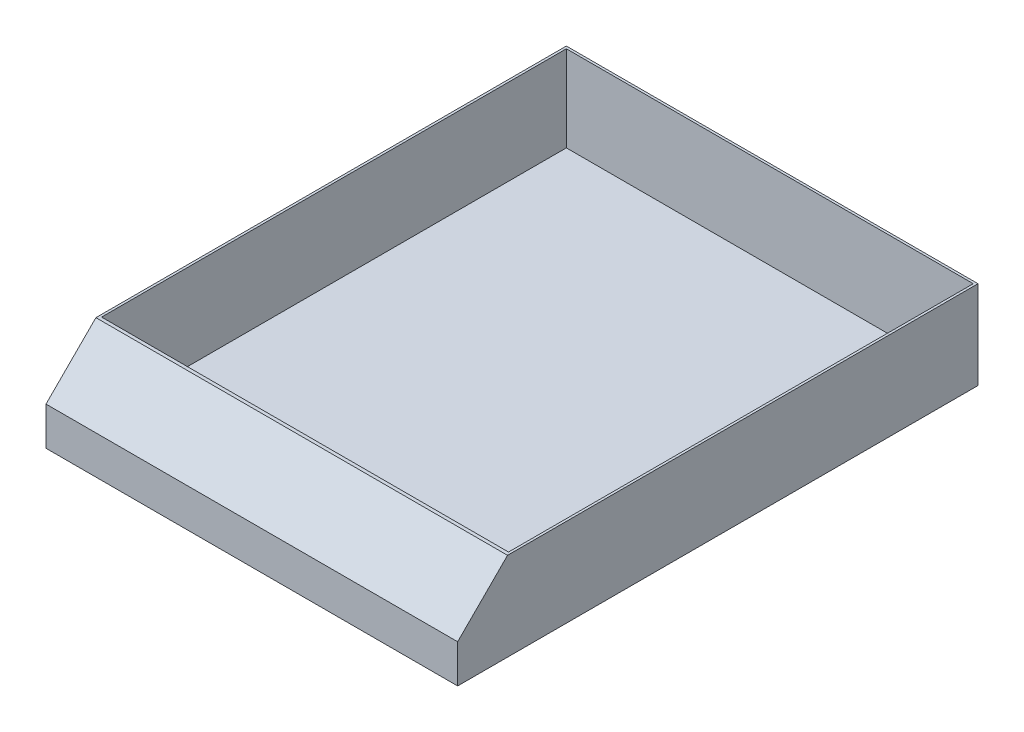
SolidWorks part; units mm, degrees
ref_plane "Front Plane" through (0, 0, 0) normal (0, 0, 1) x (1, 0, 0)
ref_plane "Top Plane" through (0, 0, 0) normal (0, 1, 0) x (1, 0, 0)
ref_plane "Right Plane" through (0, 0, 0) normal (1, 0, 0) x (0, 0, -1)
sketch "Sketch2" plane through (0, 0, 0) normal (1, 0, 0) x (0, 0, -1)
  line L0 (0, 0) -> (0, 65.1472)
  line L1 (0, 65.1472) -> (84.8528, 150)
  line L2 (84.8528, 150) -> (884.8528, 150)
  line L3 (884.8528, 150) -> (884.8528, 0)
  line L4 (884.8528, 0) -> (0, 0)
  dimension "D1" = 800
  dimension "D2" = 150
  dimension "D3" = 135
  dimension "D4" = 120
extrude "Boss-Extrude1" add sketch "Sketch2" along normal blind 700
shell "Shell1" thickness 4
